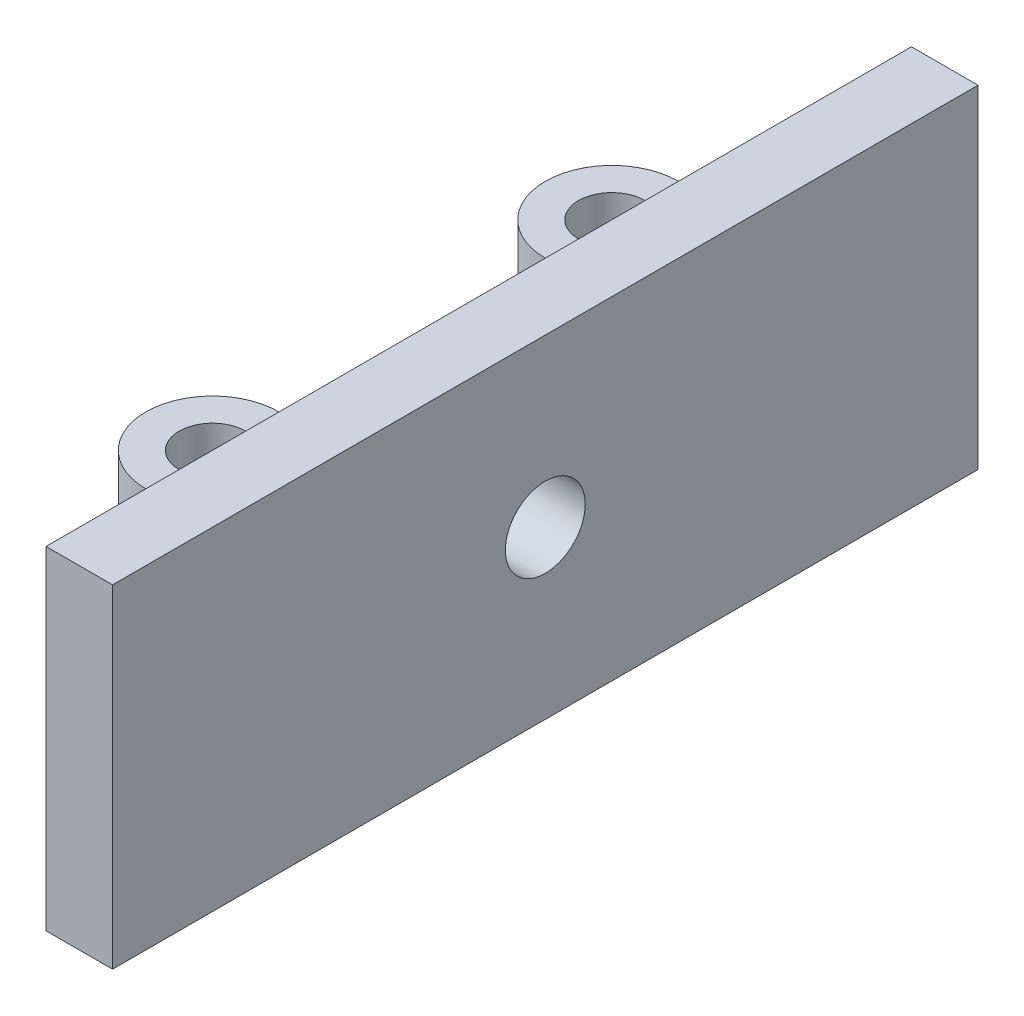
SolidWorks part; units mm, degrees
material "1023 Carbon Steel Sheet (SS)"
ref_plane "Front Plane" through (0, 0, 0) normal (0, 0, 1) x (1, 0, 0)
ref_plane "Top Plane" through (0, 0, 0) normal (0, 1, 0) x (1, 0, 0)
ref_plane "Right Plane" through (0, 0, 0) normal (1, 0, 0) x (0, 0, -1)
sketch "Sketch1" plane through (0, 0, 0) normal (0, 1, 0) x (1, 0, 0)
  line L0 (-10, 10) -> (-5, 10)
  line L1 (0, 32.5) -> (-5, 32.5)
  line L2 (0, 32.5) -> (0, -32.5)
  line L3 (-5, 32.5) -> (-5, 20)
  line L4 (-5, 10) -> (-5, -10)
  line L5 (-10, 20) -> (-5, 20)
  line L6 (-10, -10) -> (-5, -10)
  line L7 (-10, -20) -> (-5, -20)
  line L8 (0, -32.5) -> (-5, -32.5)
  line L9 (-5, -32.5) -> (-5, -20)
  arc A0 (-10, 20) -> (-10, 10) centre (-10, 15) ccw
  arc A1 (-10, -10) -> (-10, -20) centre (-10, -15) ccw
  circle A2 centre (-10, 15) radius 2.5
  circle A3 centre (-10, -15) radius 2.5
  dimension "D5" = 10
  dimension "D7" = 5
  dimension "D1" = 5
  dimension "D2" = 65
  dimension "D3" = 15
  dimension "D4" = 15
  dimension "D6" = 5
extrude "Boss-Extrude1" add sketch "Sketch1" along normal mid plane 25
sketch "Sketch2" plane through (0, 0, 0) normal (0, 0, 1) x (1, 0, 0)
  line L0 (-5, 12.5) -> (-5, -12.5) construction
  line L6 (-5, 12.5) -> (-5, -12.5) construction
  line L7 (-15, 12.5) -> (-5, 12.5)
  line L8 (-15, 12.5) -> (-15, 7.5)
  line L9 (-15, 7.5) -> (-5, 7.5)
  line L10 (-5, 12.5) -> (-5, 7.5)
  line L12 (-15, -12.5) -> (-5, -12.5)
  line L13 (-15, -12.5) -> (-15, -7.5)
  line L14 (-15, -7.5) -> (-5, -7.5)
  line L15 (-5, -12.5) -> (-5, -7.5)
  dimension "D1" = 7.5
  dimension "D2" = 7.5
extrude "Cut-Extrude1" cut sketch "Sketch2" against normal through all both and the other way through all
hole_wizard "Ø6.0mm Dowel Hole1" positions "Sketch4" profile "Sketch5" hole size "Ø6.0" standard "ISO" end condition up to next
sketch "Sketch4" plane through (0, 0, 0) normal (1, 0, 0) x (0, 0, -1)
  point P0 (0, 0)
sketch "Sketch5" plane through (0, 0, 0) normal (0, 1, 0) x (0, 0, -1)
  line L0 (0, 0) -> (0, 5)
  line L1 (0, 5) -> (3, 5)
  line L2 (3, 5) -> (3, 0)
  line L5 (3, 0) -> (0, 0)
  line L11 (0, -6.35) -> (0, 107.95) construction
  dimension "Thru Hole Dia." = 6
  dimension "Thru Hole Depth" = 5
